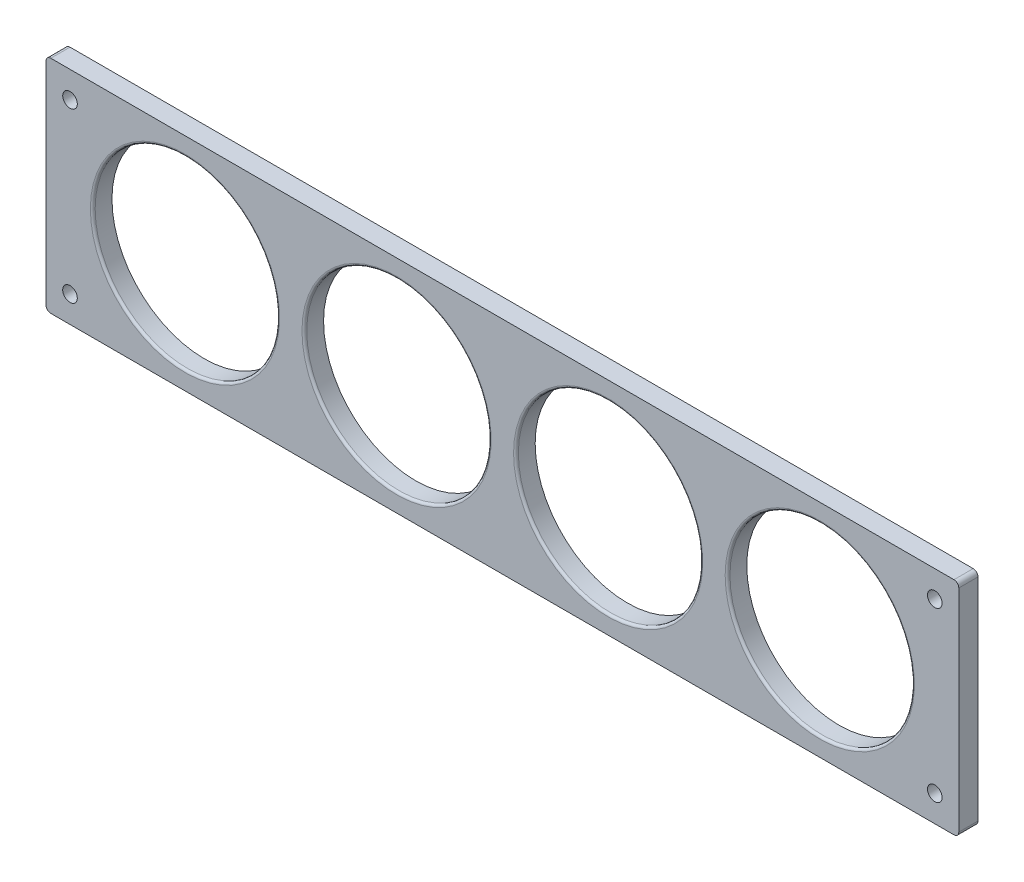
SolidWorks part; units mm, degrees
ref_plane "Plan de face" through (0, 0, 0) normal (0, 0, 1) x (1, 0, 0)
ref_plane "Plan de dessus" through (0, 0, 0) normal (0, 1, 0) x (1, 0, 0)
ref_plane "Plan de droite" through (0, 0, 0) normal (1, 0, 0) x (0, 0, -1)
sketch "Esquisse1" plane through (0, 0, 0) normal (0, 0, 1) x (1, 0, 0)
  line L0 (0, 0) -> (132.1378, 0) construction
  line L2 (-28.9311, -23) -> (161.0689, -23)
  line L3 (-28.9311, -23) -> (-28.9311, 23)
  line L4 (-28.9311, 23) -> (161.0689, 23)
  line L5 (161.0689, -23) -> (161.0689, 23)
  line L6 (-28.9311, -23) -> (161.0689, 23) construction
  line L7 (-28.9311, 23) -> (161.0689, -23) construction
  circle A0 centre (0, 0) radius 19.2
  circle A1 centre (44.0459, 0) radius 19.2
  circle A2 centre (88.0918, 0) radius 19.2
  circle A3 centre (132.1378, 0) radius 19.2
  point P3 (66.0689, 0)
  dimension "D1" = 4
  dimension "D4" = 38.4
  dimension "D2" = 190
  dimension "D3" = 46
extrude "Boss.-Extru.1" add sketch "Esquisse1" along normal blind 4
sketch "Esquisse2" plane through (0, 0, 4) normal (0, 0, 1) x (1, 0, 0)
  line L0 (-28.9311, 23) -> (-23.9353, 23) construction
  line L1 (161.0689, 23) -> (-28.9311, 23) construction
  line L2 (-23.9353, 23) -> (-23.9353, 17.4994) construction
  line L3 (-28.9311, 0) -> (0, 0) construction
  line L4 (-28.9311, 23) -> (-28.9311, -23) construction
  line L5 (-23.9353, -23) -> (-23.9353, -17.4994) construction
  line L6 (-28.9311, -23) -> (-23.9353, -23) construction
  line L7 (66.0689, 23) -> (66.0689, 48.7405) construction
  line L8 (161.0689, -23) -> (156.0731, -23) construction
  line L9 (156.0731, -23) -> (156.0731, -17.4994) construction
  line L10 (156.0731, 23) -> (156.0731, 17.4994) construction
  line L11 (161.0689, 23) -> (156.0731, 23) construction
  circle A0 centre (-23.9353, 17.4994) radius 1.52
  circle A1 centre (-23.9353, -17.4994) radius 1.52
  circle A2 centre (156.0731, -17.4994) radius 1.52
  circle A3 centre (156.0731, 17.4994) radius 1.52
extrude "Enlèv. mat.-Extru.1" cut sketch "Esquisse2" against normal blind 5
fillet "Congé2" radius 1 4 edges at (161.0689, -23, 2) (161.0689, 23, 2) (-28.9311, 23, 2) (-28.9311, -23, 2)
fillet "Congé3" radius 0.5 4 edges at (151.3378, 0, 4) (107.2918, 0, 4) (63.2459, 0, 4) (19.2, 0, 4)
